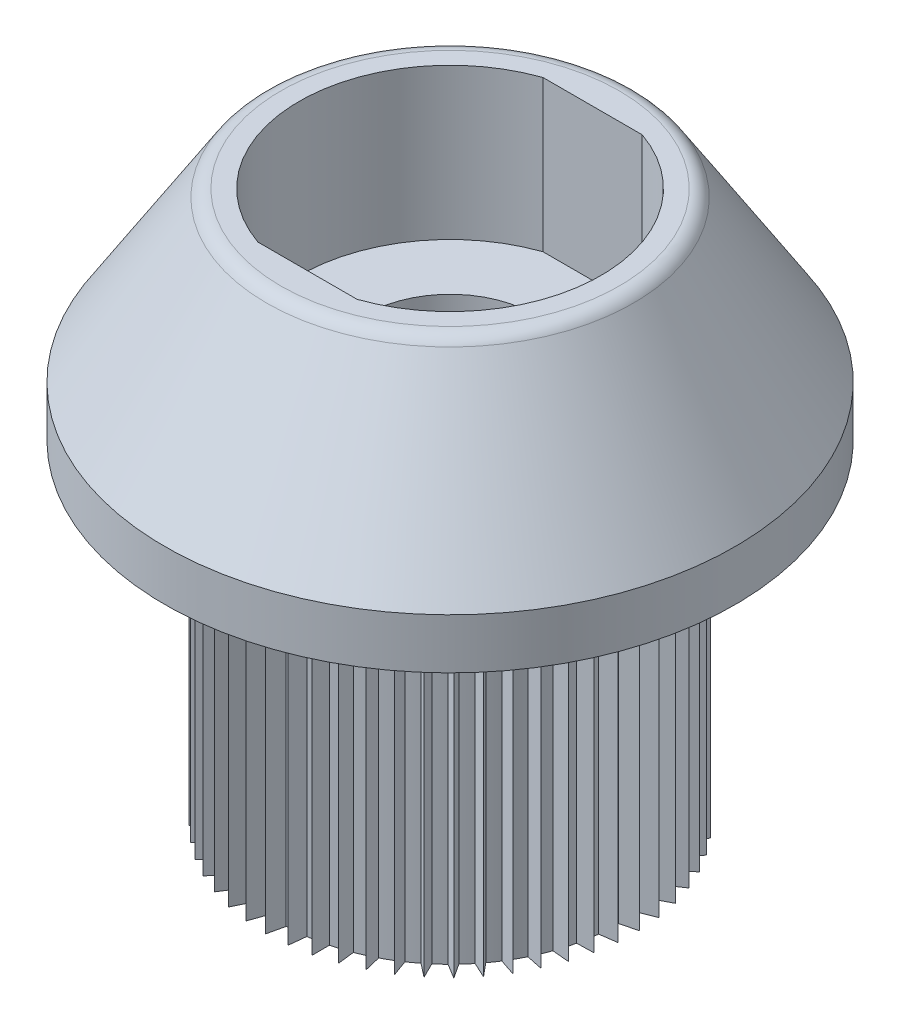
SolidWorks part; units mm, degrees
ref_plane "Спереди" through (0, 0, 0) normal (0, 0, 1) x (1, 0, 0)
ref_plane "Сверху" through (0, 0, 0) normal (0, 1, 0) x (1, 0, 0)
ref_plane "Справа" through (0, 0, 0) normal (1, 0, 0) x (0, 0, -1)
sketch "Эскиз1" plane through (0, 0, 0) normal (0, 0, 1) x (1, 0, 0)
  line L0 (-5, 17) -> (-4.5, 17)
  line L1 (-4.5, 17) -> (-4.5, 12)
  line L2 (-5, 17) -> (-8.5, 11.5)
  line L3 (-8.5, 11.5) -> (-8.5, 10)
  line L4 (-8.5, 10) -> (-5, 10)
  line L5 (-5, 10) -> (-5, 0)
  line L6 (-5, 0) -> (-2.5, 0)
  line L7 (-4.5, 12) -> (-2.5, 12)
  line L8 (-2.5, 12) -> (-2.5, 0)
  dimension "D1" = 2.5
  dimension "D2" = 5
  dimension "D3" = 17
  dimension "D4" = 4.5
  dimension "D5" = 5
  dimension "D6" = 7
  dimension "D7" = 1.5
  dimension "D8" = 5
  dimension "D9" = 8.5
ref_axis "Ось1" through (0, -50, 0) along (0, 1, 0)
revolve "Повернуть1" add sketch "Эскиз1" angle 360 about axis through (0, -50, 0) along (0, 1, 0)
sketch "Эскиз2" plane through (0, 0, 0) normal (0, -1, 0) x (1, 0, 0)
  line L0 (-0.25, 4.3997) -> (0, 5.5)
  line L1 (0, 5.5) -> (0.25, 4.3997)
  line L2 (0.25, 4.3997) -> (-0.25, 4.3997)
  dimension "D1" = 0.5
  dimension "D2" = 5.5
extrude "Бобышка-Вытянуть1" add sketch "Эскиз2" against normal blind 10
pattern_circular "Круговой массив1" count 55 over 360 about axis through (0, 0, 0) along (0, 1, 0) of "Бобышка-Вытянуть1"
sketch "Эскиз3" plane through (0, 17, 0) normal (0, 1, 0) x (1, 0, 0)
  line L0 (-1.479, 4.25) -> (1.479, 4.25)
  line L4 (-1.479, -4.25) -> (1.479, -4.25)
  circle A0 centre (0, 0) radius 4.5 construction
  circle A1 centre (0, 0) radius 4.5 construction
  arc A2 (-1.479, 4.25) -> (1.479, 4.25) centre (0, 0) cw
  arc A3 (-1.479, -4.25) -> (1.479, -4.25) centre (0, 0) ccw
  dimension "D1" = 8.5
extrude "Бобышка-Вытянуть2" add sketch "Эскиз3" against normal blind 6
sketch "Эскиз4" plane through (0, 17, 0) normal (0, 1, 0) x (1, 0, 0)
  circle A0 centre (0, 0) radius 7
extrude "Вырез-Вытянуть1" cut sketch "Эскиз4" against normal blind 0.5
fillet "Скругление2" radius 0.5 1 edges at (0, 16.5, 5.3182)
